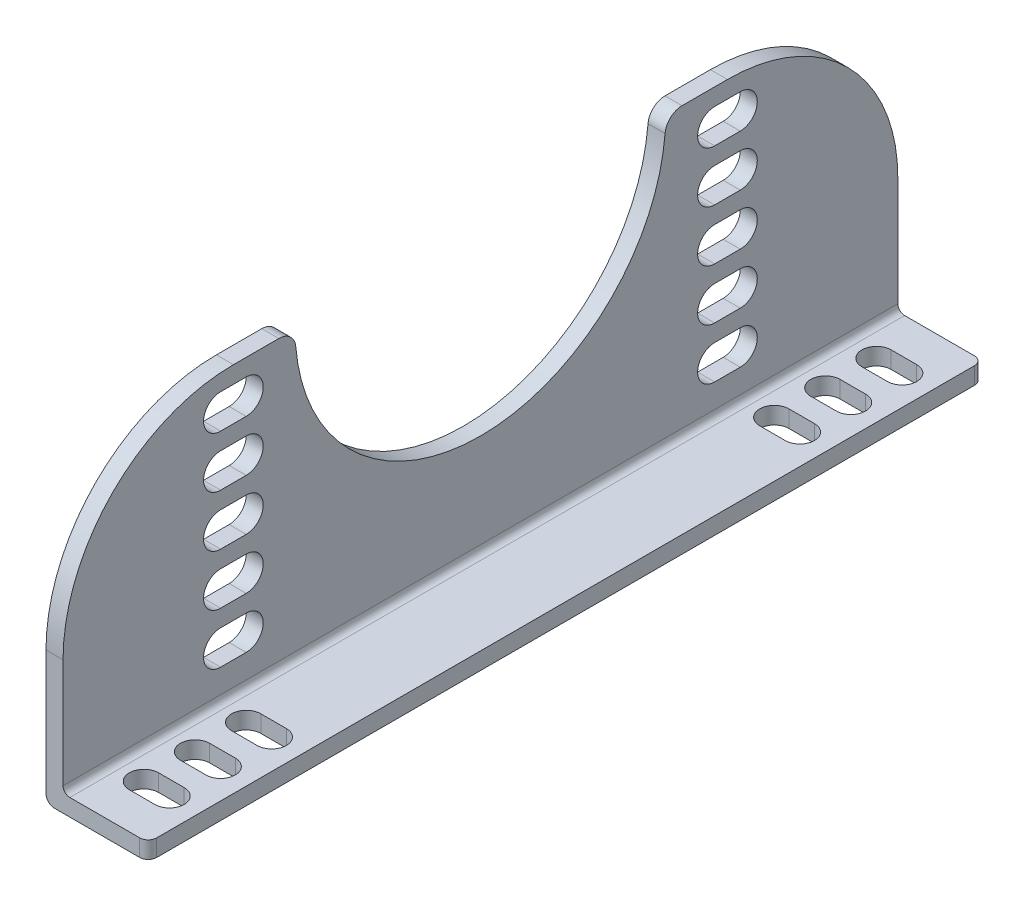
SolidWorks part; units mm, degrees
material "PA9"
ref_plane "Płaszczyzna przednia" through (0, 0, 0) normal (0, 0, 1) x (1, 0, 0)
ref_plane "Płaszczyzna górna" through (0, 0, 0) normal (0, 1, 0) x (1, 0, 0)
ref_plane "Płaszczyzna prawa" through (0, 0, 0) normal (1, 0, 0) x (0, 0, -1)
sketch "Szkic1" plane through (0, 0, 0) normal (0, 0, 1) x (1, 0, 0)
  line L1 (0, 0) -> (-10, 0)
  line L2 (0, 0) -> (0, 178)
  line L3 (0, 178) -> (-10, 178)
  line L4 (-10, 0) -> (-10, 178)
  dimension "D1" = 10
  dimension "D2" = 178
extrude "Dodanie-wyciągnięcie1" add sketch "Szkic1" along normal blind 490
sketch "Szkic2" plane through (0, 0, 0) normal (1, 0, 0) x (0, 0, -1)
  line L0 (-107.5, 158) -> (-92.5, 158) construction
  line L1 (-107.5, 168) -> (-92.5, 168)
  line L2 (-107.5, 148) -> (-92.5, 148)
  line L3 (-490, 178) -> (0, 178) construction
  line L5 (-107.5, 128) -> (-92.5, 128) construction
  line L6 (-107.5, 138) -> (-92.5, 138)
  line L7 (-107.5, 118) -> (-92.5, 118)
  line L8 (-107.5, 98) -> (-92.5, 98) construction
  line L9 (-107.5, 108) -> (-92.5, 108)
  line L10 (-107.5, 88) -> (-92.5, 88)
  line L11 (-107.5, 68) -> (-92.5, 68) construction
  line L12 (-107.5, 78) -> (-92.5, 78)
  line L13 (-107.5, 58) -> (-92.5, 58)
  line L14 (-107.5, 38) -> (-92.5, 38) construction
  line L15 (-107.5, 48) -> (-92.5, 48)
  line L16 (-107.5, 28) -> (-92.5, 28)
  line L17 (0, 0) -> (0, 178) construction
  arc A0 (-107.5, 168) -> (-107.5, 148) centre (-107.5, 158) ccw
  arc A1 (-92.5, 148) -> (-92.5, 168) centre (-92.5, 158) ccw
  arc A2 (-107.5, 138) -> (-107.5, 118) centre (-107.5, 128) ccw
  arc A3 (-92.5, 118) -> (-92.5, 138) centre (-92.5, 128) ccw
  arc A4 (-107.5, 108) -> (-107.5, 88) centre (-107.5, 98) ccw
  arc A5 (-92.5, 88) -> (-92.5, 108) centre (-92.5, 98) ccw
  arc A6 (-107.5, 78) -> (-107.5, 58) centre (-107.5, 68) ccw
  arc A7 (-92.5, 58) -> (-92.5, 78) centre (-92.5, 68) ccw
  arc A8 (-107.5, 48) -> (-107.5, 28) centre (-107.5, 38) ccw
  arc A9 (-92.5, 28) -> (-92.5, 48) centre (-92.5, 38) ccw
  point P2 (-100, 158)
  point P15 (-100, 128)
  point P22 (-100, 98)
  point P29 (-100, 68)
  point P36 (-100, 38)
  dimension "D1" = 10
  dimension "D2" = 15
  dimension "D3" = 20
  dimension "D4" = 100
  dimension "D6" = 30
  dimension "D5" = 5
extrude "Wytnij-wyciągnięcie1" cut sketch "Szkic2" against normal through all
sketch "Szkic3" plane through (0, 0, 0) normal (1, 0, 0) x (0, 0, -1)
  line L0 (-397.5, 158) -> (-382.5, 158) construction
  line L1 (-397.5, 168) -> (-382.5, 168)
  line L2 (-397.5, 148) -> (-382.5, 148)
  line L3 (-490, 178) -> (0, 178) construction
  line L4 (-92.5, 168) -> (-107.5, 168) construction
  line L5 (-397.5, 128) -> (-382.5, 128) construction
  line L6 (-397.5, 138) -> (-382.5, 138)
  line L7 (-397.5, 118) -> (-382.5, 118)
  line L8 (-397.5, 98) -> (-382.5, 98) construction
  line L9 (-397.5, 108) -> (-382.5, 108)
  line L10 (-397.5, 88) -> (-382.5, 88)
  line L11 (-397.5, 68) -> (-382.5, 68) construction
  line L12 (-397.5, 78) -> (-382.5, 78)
  line L13 (-397.5, 58) -> (-382.5, 58)
  line L14 (-397.5, 38) -> (-382.5, 38) construction
  line L15 (-397.5, 48) -> (-382.5, 48)
  line L16 (-397.5, 28) -> (-382.5, 28)
  arc A0 (-397.5, 168) -> (-397.5, 148) centre (-397.5, 158) ccw
  arc A1 (-382.5, 148) -> (-382.5, 168) centre (-382.5, 158) ccw
  arc A2 (-397.5, 138) -> (-397.5, 118) centre (-397.5, 128) ccw
  arc A3 (-382.5, 118) -> (-382.5, 138) centre (-382.5, 128) ccw
  arc A4 (-397.5, 108) -> (-397.5, 88) centre (-397.5, 98) ccw
  arc A5 (-382.5, 88) -> (-382.5, 108) centre (-382.5, 98) ccw
  arc A6 (-397.5, 78) -> (-397.5, 58) centre (-397.5, 68) ccw
  arc A7 (-382.5, 58) -> (-382.5, 78) centre (-382.5, 68) ccw
  arc A8 (-397.5, 48) -> (-397.5, 28) centre (-397.5, 38) ccw
  arc A9 (-382.5, 28) -> (-382.5, 48) centre (-382.5, 38) ccw
  point P2 (-390, 158)
  point P11 (-100, 168)
  point P15 (-390, 128)
  point P22 (-390, 98)
  point P29 (-390, 68)
  point P36 (-390, 38)
  dimension "D1" = 10
  dimension "D2" = 15
  dimension "D3" = 20
  dimension "D4" = 290
  dimension "D5" = 5
extrude "Wytnij-wyciągnięcie2" cut sketch "Szkic3" against normal through all
fillet "Zaokrąglenie1" radius 100 1 edges at (-5, 178, 0)
fillet "Zaokrąglenie2" radius 100 1 edges at (-5, 178, 490)
sketch "Szkic5" plane through (-10, 0, 0) normal (-1, 0, 0) x (0, 0, 1)
  line L0 (390, 178) -> (100, 178) construction
  line L1 (136.2352, 178) -> (353.7648, 178)
  arc A0 (136.2352, 178) -> (353.7648, 178) centre (245, 178) ccw
extrude "Wytnij-wyciągnięcie3" cut sketch "Szkic5" against normal through all
fillet "Zaokrąglenie3" radius 10 2 edges at (-5, 178, 353.7648) (-5, 178, 136.2352)
sketch "Szkic6" plane through (0, 0, 0) normal (0, 0, -1) x (-1, 0, 0)
  line L1 (10, 0) -> (-50, 0)
  line L2 (10, 0) -> (10, 10)
  line L3 (10, 10) -> (-50, 10)
  line L4 (-50, 0) -> (-50, 10)
  dimension "D1" = 60
  dimension "D2" = 10
extrude "Dodanie-wyciągnięcie2" add sketch "Szkic6" against normal through all
fillet "Zaokrąglenie4" radius 5 1 edges at (-10, 0, 245)
fillet "Zaokrąglenie5" radius 4 1 edges at (0, 10, 245)
fillet "Zaokrąglenie6" radius 5 2 edges at (50, 5, 0) (50, 5, 490)
sketch "Szkic7" plane through (0, 10, 0) normal (0, 1, 0) x (1, 0, 0)
  line L0 (32.5, -460) -> (17.5, -460) construction
  line L1 (32.5, -468.6) -> (17.5, -468.6)
  line L2 (32.5, -451.4) -> (17.5, -451.4)
  line L3 (4, -490) -> (45, -490) construction
  line L4 (50, -485) -> (50, -5) construction
  arc A0 (32.5, -468.6) -> (32.5, -451.4) centre (32.5, -460) ccw
  arc A1 (17.5, -451.4) -> (17.5, -468.6) centre (17.5, -460) ccw
  point P2 (25, -460)
  dimension "D2" = 8.6
  dimension "D1" = 15
  dimension "D3" = 30
  dimension "D4" = 25
extrude "Wytnij-wyciągnięcie4" cut sketch "Szkic7" against normal blind 10
ref_plane "Płaszczyzna1" through (0, 0, 245) normal (0, 0, -1) x (-1, 0, 0)
mirror "Lustro2" about plane through (0, 0, 245) normal (0, 0, -1) of "Wytnij-wyciągnięcie4"
sketch "Szkic8" plane through (0, 10, 0) normal (0, 1, 0) x (1, 0, 0)
  line L3 (50, -485) -> (50, -5) construction
  line L5 (17.5, -430) -> (32.5, -430) construction
  line L6 (17.5, -421.4) -> (32.5, -421.4)
  line L7 (17.5, -438.6) -> (32.5, -438.6)
  line L8 (4, -490) -> (45, -490) construction
  arc A2 (17.5, -421.4) -> (17.5, -438.6) centre (17.5, -430) ccw
  arc A3 (32.5, -438.6) -> (32.5, -421.4) centre (32.5, -430) ccw
  point P13 (25, -430)
  dimension "D7" = 8.6
  dimension "D5" = 60
  dimension "D6" = 15
  dimension "D8" = 25
extrude "Wytnij-wyciągnięcie5" cut sketch "Szkic8" against normal blind 10
mirror "Lustro3" about plane through (0, 0, 245) normal (0, 0, -1) of "Wytnij-wyciągnięcie5"
sketch "Szkic9" plane through (0, 10, 0) normal (0, 1, 0) x (1, 0, 0)
  line L0 (17.5, -400) -> (32.5, -400) construction
  line L1 (17.5, -391.4) -> (32.5, -391.4)
  line L2 (17.5, -408.6) -> (32.5, -408.6)
  line L3 (50, -485) -> (50, -5) construction
  line L4 (4, -490) -> (45, -490) construction
  arc A0 (17.5, -391.4) -> (17.5, -408.6) centre (17.5, -400) ccw
  arc A1 (32.5, -408.6) -> (32.5, -391.4) centre (32.5, -400) ccw
  point P2 (25, -400)
  dimension "D2" = 8.6
  dimension "D1" = 15
  dimension "D3" = 25
  dimension "D4" = 90
extrude "Wytnij-wyciągnięcie6" cut sketch "Szkic9" against normal blind 10
mirror "Lustro4" about plane through (0, 0, 245) normal (0, 0, -1) of "Wytnij-wyciągnięcie6"
